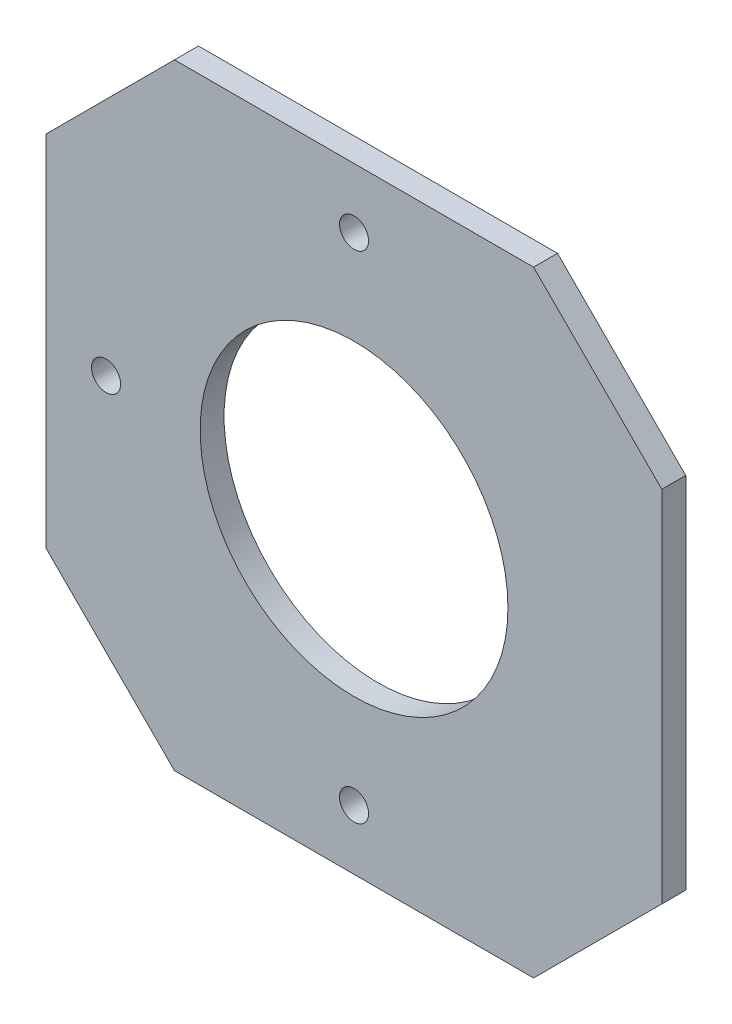
SolidWorks part; units mm, degrees
ref_plane "Спереди" through (0, 0, 0) normal (0, 0, 1) x (1, 0, 0)
ref_plane "Сверху" through (0, 0, 0) normal (0, 1, 0) x (1, 0, 0)
ref_plane "Справа" through (0, 0, 0) normal (1, 0, 0) x (0, 0, -1)
other "Configuration Table"
sketch "Эскиз1" plane through (0, 0, 0) normal (0, 0, 1) x (1, 0, 0)
  line L0 (-21, -36) -> (21, -36)
  line L1 (21, -36) -> (36, -21)
  line L2 (36, -21) -> (36, 21)
  line L3 (36, 21) -> (21, 36)
  line L4 (21, 36) -> (-21, 36)
  line L5 (-21, 36) -> (-36, 21)
  line L6 (-36, 21) -> (-36, -21)
  line L7 (-36, -21) -> (-21, -36)
  circle A0 centre (0, 0) radius 18
  circle A1 centre (0, 29) radius 1.7
  circle A2 centre (0, -29) radius 1.7
  circle A3 centre (-29, 0) radius 1.7
extrude "04_Bearing_retainer" add sketch "Эскиз1" along normal blind 2.8
